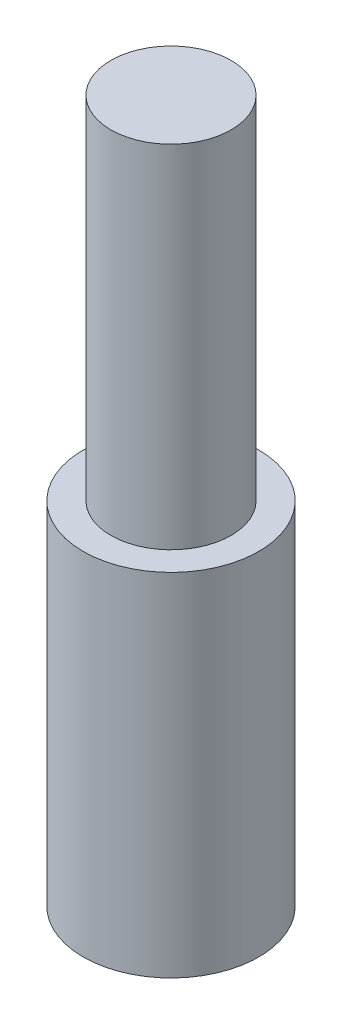
SolidWorks part; units mm, degrees
material "PUR"
ref_plane "Z" through (0, 0, 0) normal (0, 0, 1) x (1, 0, 0)
ref_plane "Y" through (0, 0, 0) normal (0, 1, 0) x (1, 0, 0)
ref_plane "X" through (0, 0, 0) normal (1, 0, 0) x (0, 0, -1)
sketch "Sketch1" plane through (0, 0, 0) normal (0, 1, 0) x (1, 0, 0)
  circle A0 centre (0, 0) radius 4.7625
  dimension "D1" = 9.525
extrude "Boss-Extrude1" add sketch "Sketch1" along normal blind 38.1
sketch "Sketch2" plane through (0, 38.1, 0) normal (0, 1, 0) x (1, 0, 0)
  circle A1 centre (0, 0) radius 5.5679
  circle A2 centre (0, 0) radius 3.2625
  circle A3 centre (0, 0) radius 3.2625
  dimension "D1" = 1.5
extrude "Cut-Extrude1" cut sketch "Sketch2" against normal blind 19.05
